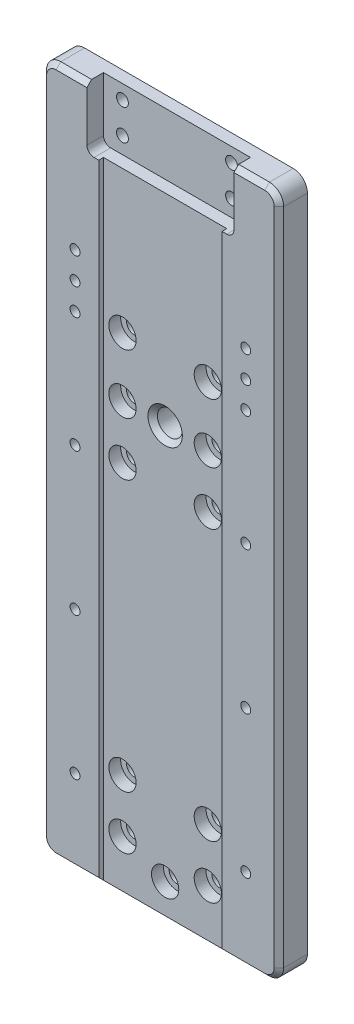
SolidWorks part; units mm, degrees
material "1060 Alloy"
ref_plane "Front Plane" through (0, 0, 0) normal (0, 0, 1) x (1, 0, 0)
ref_plane "Top Plane" through (0, 0, 0) normal (0, 1, 0) x (1, 0, 0)
ref_plane "Right Plane" through (0, 0, 0) normal (1, 0, 0) x (0, 0, -1)
sketch "Sketch1" plane through (0, 0, 0) normal (0, 0, 1) x (1, 0, 0)
  line L1 (50, -145) -> (-50, -145)
  line L2 (50, -145) -> (50, 145)
  line L3 (50, 145) -> (-50, 145)
  line L4 (-50, -145) -> (-50, 145)
  line L5 (50, -145) -> (-50, 145) construction
  line L6 (50, 145) -> (-50, -145) construction
  point P0 (0, 0)
  dimension "D1" = 100
  dimension "D2" = 290
extrude "Boss-Extrude1" add sketch "Sketch1" along normal mid plane 12
sketch "Sketch2" plane through (0, 0, 6) normal (0, 0, 1) x (1, 0, 0)
  line L0 (0, 132) -> (0, 0) construction
  line L1 (31, 119) -> (-31, 119)
  line L2 (31, 119) -> (31, 145)
  line L3 (31, 145) -> (-31, 145)
  line L4 (-31, 119) -> (-31, 145)
  line L5 (31, 119) -> (-31, 145) construction
  line L6 (31, 145) -> (-31, 119) construction
  line L7 (50, 145) -> (-50, 145) construction
  point P0 (0, 132)
  dimension "D1" = 62
  dimension "D2" = 26
extrude "Cut-Extrude1" cut sketch "Sketch2" against normal blind 7
sketch "Sketch3" plane through (0, 0, 6) normal (0, 0, 1) x (1, 0, 0)
  line L0 (-50, -145) -> (50, -145) construction
  line L1 (26, 145) -> (-26, 145)
  line L2 (26, 145) -> (26, -145)
  line L3 (26, -145) -> (-26, -145)
  line L4 (-26, 145) -> (-26, -145)
  line L5 (26, 145) -> (-26, -145) construction
  line L6 (26, -145) -> (-26, 145) construction
  point P0 (0, 0)
  dimension "D1" = 52
extrude "Cut-Extrude2" cut sketch "Sketch3" against normal blind 2
sketch "Sketch4" plane through (0, 0, -6) normal (0, 0, 1) x (1, 0, 0)
  line L0 (0, 132.5) -> (0, 0) construction
  line L1 (23, 126) -> (-23, 126) construction
  line L2 (23, 126) -> (23, 139) construction
  line L3 (23, 139) -> (-23, 139) construction
  line L4 (-23, 126) -> (-23, 139) construction
  line L5 (23, 126) -> (-23, 139) construction
  line L6 (23, 139) -> (-23, 126) construction
  line L7 (31, 145) -> (-31, 145) construction
  line L8 (-18, 59) -> (-18, 11.5) construction
  line L9 (-36, 81.25) -> (-36, -110) construction
  line L11 (-50, -145) -> (-26, -145) construction
  line L12 (0, 0) -> (0, -145) construction
  line L13 (-26, -145) -> (26, -145) construction
  line L15 (18, -102.5) -> (-18, -102.5) construction
  line L16 (18, -102.5) -> (18, -125) construction
  line L17 (18, -125) -> (-18, -125) construction
  line L18 (-18, -102.5) -> (-18, -125) construction
  line L19 (18, -102.5) -> (-18, -125) construction
  line L20 (18, -125) -> (-18, -102.5) construction
  circle A0 centre (-23, 139) radius 2.5
  circle A1 centre (23, 139) radius 2.5
  circle A2 centre (23, 126) radius 2.5
  circle A3 centre (-23, 126) radius 2.5
  circle A4 centre (0, 34) radius 5.25
  circle A5 centre (-18, 59) radius 3.3
  circle A6 centre (-18, 34) radius 3.3
  circle A7 centre (-18, 11.5) radius 3.3
  circle A8 centre (-36, 81.25) radius 2.1
  circle A9 centre (-36, 70) radius 2.1
  circle A10 centre (-36, 58.75) radius 2.1
  circle A11 centre (-36, 10) radius 2.1
  circle A12 centre (-36, -110) radius 2.1
  circle A13 centre (-36, -50) radius 2.1
  circle A14 centre (-18, -102.5) radius 3.3
  circle A15 centre (-18, -125) radius 3.3
  circle A16 centre (18, -102.5) radius 3.3
  circle A17 centre (18, -125) radius 3.3
  circle A18 centre (0, -132.5) radius 3.3
  circle A19 centre (36, 81.25) radius 2.1
  circle A20 centre (36, 70) radius 2.1
  circle A21 centre (36, 58.75) radius 2.1
  circle A22 centre (18, 59) radius 3.3
  circle A23 centre (18, 11.5) radius 3.3
  circle A24 centre (18, 34) radius 3.3
  circle A25 centre (36, 10) radius 2.1
  circle A26 centre (36, -50) radius 2.1
  circle A27 centre (36, -110) radius 2.1
  point P0 (0, 132.5)
  point P36 (0, -113.75)
  dimension "D1" = 5
  dimension "D5" = 10.5
  dimension "D7" = 6.6
  dimension "D12" = 4.2
  dimension "D19" = 6.6
  dimension "D2" = 13
  dimension "D3" = 46
  dimension "D4" = 6
  dimension "D6" = 111
  dimension "D8" = 18
  dimension "D9" = 25
  dimension "D10" = 22.5
  dimension "D11" = 36
  dimension "D13" = 35
  dimension "D14" = 60
  dimension "D15" = 60
  dimension "D16" = 48.75
  dimension "D17" = 11.25
  dimension "D18" = 11.25
  dimension "D20" = 12.5
  dimension "D21" = 36
  dimension "D22" = 20
  dimension "D23" = 22.5
extrude "Cut-Extrude4" cut sketch "Sketch4" along normal blind 21
fillet "Fillet1" radius 3 2 edges at (31, 119, 2.5) (-31, 119, 2.5)
fillet "Fillet2" radius 6 4 edges at (50, -145, 0) (-50, -145, 0) (50, 145, 0) (-50, 145, 0)
chamfer "Chamfer1" distance 2 angle 45 10 edges at (35, -145, 6) (48.2426, -143.2426, 6) (50, 0, 6) (48.2426, 143.2426, 6) (37.5, 145, 6) (-35, -145, 6) (-48.2426, -143.2426, 6) (-50, 0, 6) (-48.2426, 143.2426, 6) (-37.5, 145, 6)
sketch "Sketch5" plane through (0, 0, 4) normal (0, 0, 1) x (1, 0, 0)
  circle A0 centre (-18, 59) radius 5.75
  circle A1 centre (-18, 34) radius 5.75
  circle A2 centre (-18, 11.5) radius 5.75
  circle A3 centre (18, 11.5) radius 5.75
  circle A4 centre (18, 34) radius 5.75
  circle A5 centre (18, 59) radius 5.75
  circle A6 centre (18, -102.5) radius 5.75
  circle A7 centre (-18, -102.5) radius 5.75
  circle A8 centre (-18, -125) radius 5.75
  circle A9 centre (0, -132.5) radius 5.75
  circle A10 centre (18, -125) radius 5.75
  dimension "D1" = 11.5
extrude "Cut-Extrude5" cut sketch "Sketch5" against normal blind 5
chamfer "Chamfer2" distance 2 angle 45 1 edges at (-5.25, 34, 4)
equation "\"M5_tap\"=4.2mm"
equation "\"M5_clearence\"=5.5mm"
equation "\"M6_tap\"=5mm"
equation "\"M6_clearence\"=6.6mm"
equation "\"D1@Sketch4\"=\"M6_tap\""
equation "\"D12@Sketch4\"=\"M5_tap\""
equation "\"D7@Sketch4\"=\"M6_clearence\""
equation "\"D19@Sketch4\"=\"M6_clearence\""
